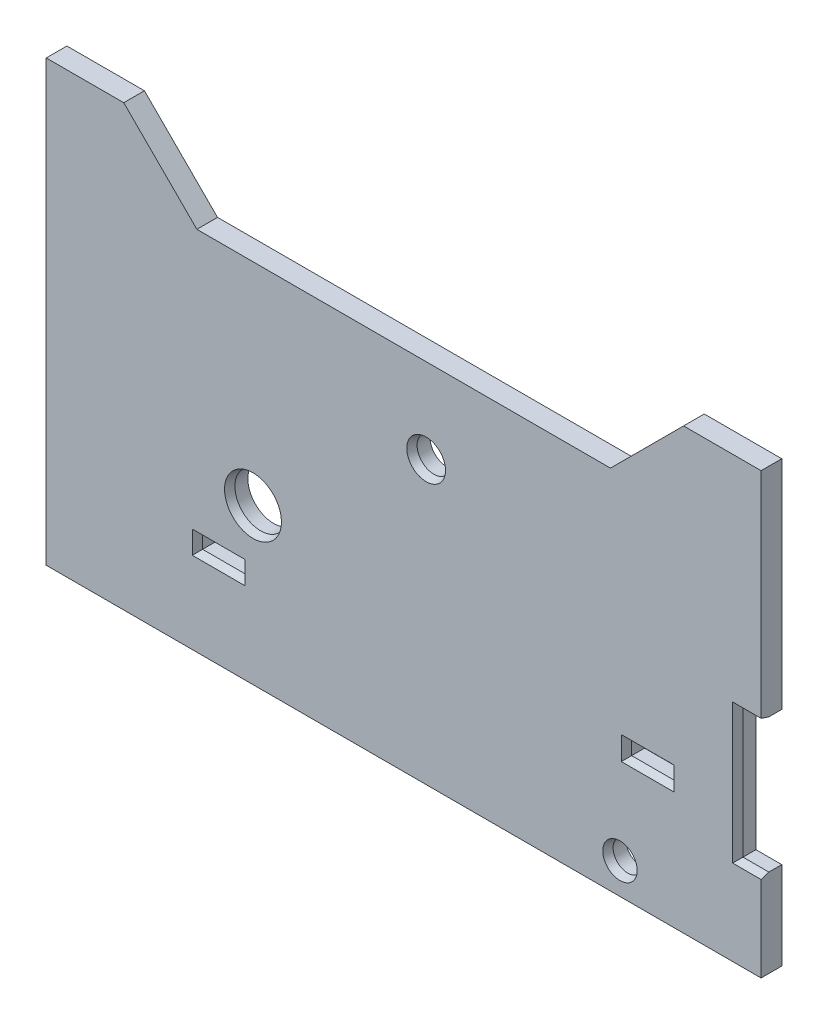
SolidWorks part; units mm, degrees
ref_plane "Front Plane" through (0, 0, 0) normal (0, 0, 1) x (1, 0, 0)
ref_plane "Top Plane" through (0, 0, 0) normal (0, 1, 0) x (1, 0, 0)
ref_plane "Right Plane" through (0, 0, 0) normal (1, 0, 0) x (0, 0, -1)
sketch "Sketch1" plane through (0, 0, 0) normal (0, 0, 1) x (1, 0, 0)
  line L2 (-86, -30) -> (-86, 30)
  line L6 (52.3, 13) -> (47.3, 13)
  line L7 (47.3, 13) -> (47.3, -13)
  line L8 (47.3, -13) -> (52.3, -13)
  line L11 (52.3, 30) -> (52.3, 13)
  line L12 (52.3, -13) -> (52.3, -30)
  line L23 (52.3, 30) -> (-86, 30)
  line L24 (25.75, -3.235) -> (34.95, -3.235)
  line L25 (25.75, -3.235) -> (25.75, -6.765)
  line L26 (25.75, -6.765) -> (34.95, -6.765)
  line L27 (34.95, -3.235) -> (34.95, -6.765)
  line L28 (25.75, -5) -> (34.95, -5) construction
  line L29 (30.35, -3.235) -> (30.35, -6.765) construction
  line L30 (-86, -30) -> (52.3, -30)
  line L31 (-48.05, -12) -> (-57.25, -12) construction
  line L32 (-57.25, -10.3) -> (-48.05, -10.3)
  line L33 (-57.25, -10.3) -> (-57.25, -13.7)
  line L34 (-57.25, -13.7) -> (-48.05, -13.7)
  line L35 (-48.05, -10.3) -> (-48.05, -13.7)
  line L36 (-52.65, -10.3) -> (-52.65, -13.83) construction
  circle A3 centre (-46, 0) radius 5
  circle A4 centre (25, -24) radius 2.83
  circle A5 centre (-12.5, 24.5) radius 3.25
  point P1 (-12, 0)
  point P33 (-52.65, -10.3)
  point P35 (-48.05, -12)
  point P36 (-57.25, -12)
  dimension "D5" = 10
  dimension "D17" = 5.66
  dimension "D25" = 6.5
  dimension "D1" = 40
  dimension "D8" = 26
  dimension "D13" = 9.2
  dimension "D14" = 3.53
  dimension "D18" = 111
  dimension "D27" = 33.5
  dimension "D28" = 24.5
  dimension "D6" = 5
  dimension "D4" = 24
  dimension "D7" = 116.35
  dimension "D9" = 60
  dimension "D3" = 138.3
  dimension "D10" = 5
  dimension "D11" = 12
  dimension "D12" = 33.35
extrude "Boss-Extrude1" add sketch "Sketch1" along normal mid plane 4
sketch "Sketch2" plane through (0, 0, 0) normal (0, 0, 1) x (1, 0, 0)
  line L0 (-86, 30) -> (52.3, 30)
  line L1 (52.3, 30) -> (52.3, 55)
  line L2 (52.3, 55) -> (37.3, 55)
  line L3 (37.3, 55) -> (23.1579, 40.8579)
  line L4 (23.1579, 40.8579) -> (-56.8579, 40.8579)
  line L5 (-56.8579, 40.8579) -> (-71, 55)
  line L6 (-71, 55) -> (-86, 55)
  line L7 (-86, 55) -> (-86, 30)
  dimension "D1" = 25
  dimension "D2" = 15
  dimension "D3" = 20
  dimension "D4" = 135
extrude "Boss-Extrude2" add sketch "Sketch2" along normal mid plane 4
sketch "Sketch3" plane through (0, 0, 2) normal (0, 0, 1) x (1, 0, 0)
  line L0 (25.75, -5) -> (34.95, -5) construction
  line L1 (25.75, -3.235) -> (25.75, -6.765) construction
  line L2 (34.95, -6.765) -> (34.95, -3.235) construction
  line L3 (30.35, -3.235) -> (30.35, -6.765) construction
  line L4 (34.95, -3.235) -> (25.75, -3.235) construction
  line L5 (25.75, -6.765) -> (34.95, -6.765) construction
  line L6 (-57.25, -12) -> (-48.05, -12) construction
  line L7 (-57.25, -10.3) -> (-57.25, -13.7) construction
  line L8 (-48.05, -13.7) -> (-48.05, -10.3) construction
  line L9 (-52.65, -10.3) -> (-52.65, -13.7) construction
  line L10 (-48.05, -10.3) -> (-57.25, -10.3) construction
  line L11 (-57.25, -13.7) -> (-48.05, -13.7) construction
sketch "Sketch4" plane through (47.3, 0, 0) normal (1, 0, 0) x (0, 0, -1)
  line L0 (-2, 0) -> (2, 0) construction
  line L1 (-2, -13) -> (-2, 13) construction
  line L2 (2, -13) -> (2, 13) construction
chamfer "Chamfer1" distance 0.5 distance2 1.5 11 edges at (27.83, -24, 2) (30.35, -6.765, 2) (25.75, -5, 2) (30.35, -3.235, 2) (34.95, -5, 2) (-48.05, -12, 2) (-52.65, -13.7, 2) (-57.25, -12, 2) (-52.65, -10.3, 2) (-41, 0, 2) (-9.25, 24.5, 2)
chamfer "Chamfer2" distance 1.5 distance2 0.5 3 edges at (49.8, -13, 2) (47.3, 0, 2) (49.8, 13, 2)
equation "\"back_boost\"= 7"
equation "\"D18@Sketch1\"=\"back_boost\"+104.00mm"
equation "\"D1@Sketch1\"=33.00mm+\"back_boost\""
equation "\"D7@Sketch1\"=109.35mm+\"back_boost\""
equation "\"D3@Sketch1\"=131.30mm+\"back_boost\""
equation "\"D12@Sketch1\"=\"back_boost\"+26.35mm"
equation "\"pin_hole_height\"=9.2"
equation "\"D13@Sketch1\"=\"pin_hole_height\""
equation "\"pin_hole_width\"=3.53"
equation "\"D14@Sketch1\"=\"pin_hole_width\""
